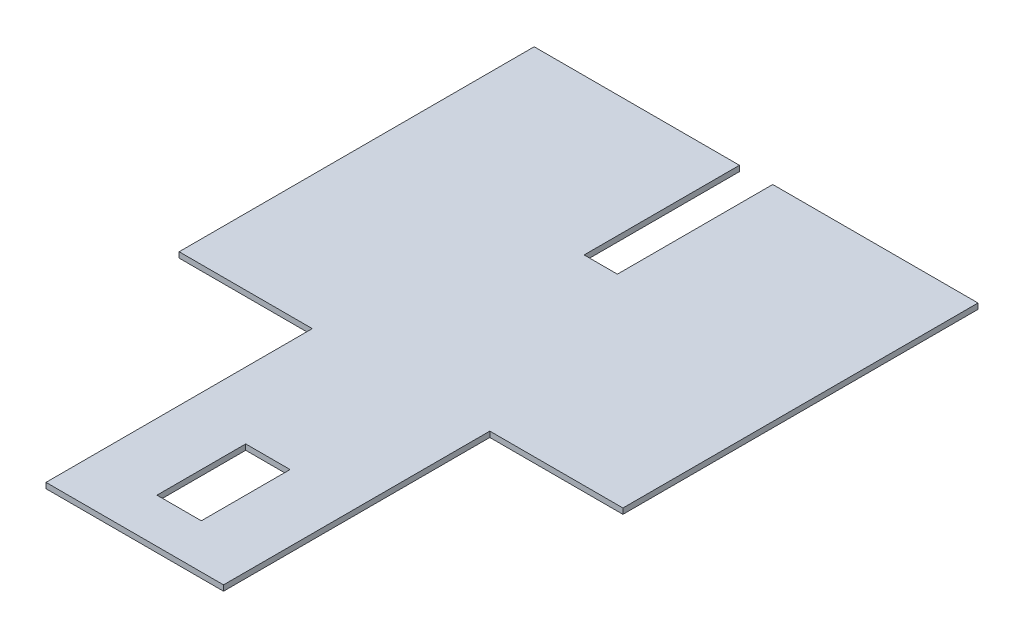
SolidWorks part; units mm, degrees
ref_plane "Front Plane" through (0, 0, 0) normal (0, 0, 1) x (1, 0, 0)
ref_plane "Top Plane" through (0, 0, 0) normal (0, 1, 0) x (1, 0, 0)
ref_plane "Right Plane" through (0, 0, 0) normal (1, 0, 0) x (0, 0, -1)
sketch "Sketch1" plane through (0, 0, 0) normal (0, 1, 0) x (1, 0, 0)
  line L0 (-63.5, -12.7) -> (-25.4, -12.7)
  line L1 (-63.5, 88.9) -> (63.5, 88.9)
  line L2 (-63.5, 88.9) -> (-63.5, -12.7)
  line L3 (-25.4, -88.9) -> (25.4, -88.9)
  line L4 (63.5, 88.9) -> (63.5, -12.7)
  line L5 (-25.4, -12.7) -> (-25.4, -88.9)
  line L6 (25.4, -88.9) -> (25.4, -12.7)
  line L7 (25.4, -12.7) -> (63.5, -12.7)
  dimension "D1" = 177.8
  dimension "D2" = 127
  dimension "D3" = 63.5
  dimension "D4" = 88.9
  dimension "D5" = 38.1
  dimension "D6" = 38.1
  dimension "D7" = 76.2
  dimension "D8" = 76.2
extrude "Boss-Extrude1" add sketch "Sketch1" along normal blind 1.5875
sketch "Sketch2" plane through (0, 1.5875, 0) normal (0, 1, 0) x (1, 0, 0)
  line L0 (-25.4, -88.9) -> (25.4, -88.9) construction
  line L1 (6.35, -76.2) -> (-6.35, -76.2)
  line L2 (6.35, -76.2) -> (6.35, -50.8)
  line L3 (6.35, -50.8) -> (-6.35, -50.8)
  line L4 (-6.35, -76.2) -> (-6.35, -50.8)
  line L5 (0, -88.9) -> (0, -14.7556) construction
  dimension "D1" = 12.7
  dimension "D2" = 12.7
  dimension "D3" = 25.4
  dimension "D4" = 6.35
extrude "Cut-Extrude1" cut sketch "Sketch2" against normal up to next
sketch "Sketch3" plane through (0, 1.5875, 0) normal (0, 1, 0) x (1, 0, 0)
  line L0 (0, 104.8529) -> (0, -142.2419) construction
  line L1 (63.5, 88.9) -> (-63.5, 88.9) construction
  line L2 (-4.7625, 88.9) -> (4.7625, 88.9)
  line L3 (-4.7625, 88.9) -> (-4.7625, 44.45)
  line L4 (-4.7625, 44.45) -> (4.7625, 44.45)
  line L5 (4.7625, 88.9) -> (4.7625, 44.45)
  dimension "D1" = 9.525
  dimension "D2" = 44.45
  dimension "D3" = 4.7625
extrude "Cut-Extrude2" cut sketch "Sketch3" against normal up to next
